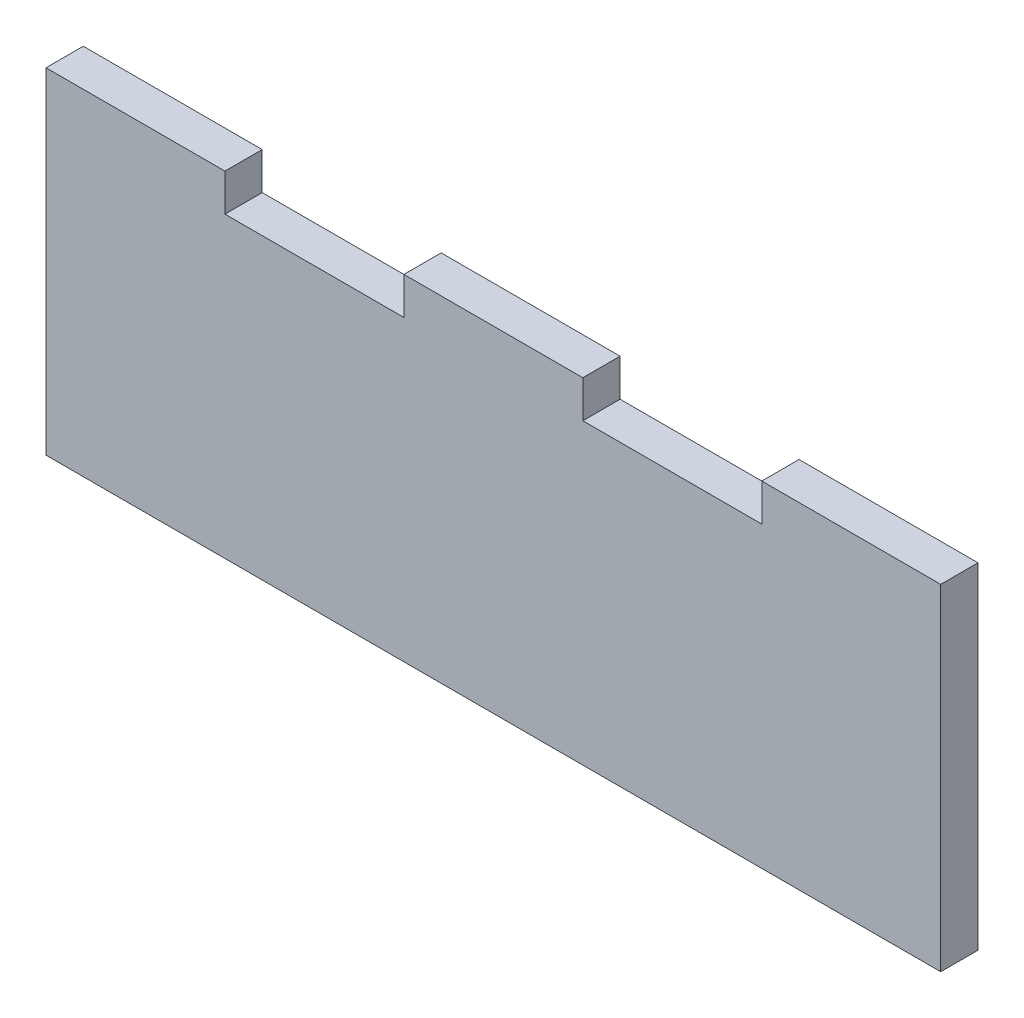
SolidWorks part; units mm, degrees
material "Pine"
ref_plane "Front Plane" through (0, 0, 0) normal (0, 0, 1) x (1, 0, 0)
ref_plane "Top Plane" through (0, 0, 0) normal (0, 1, 0) x (1, 0, 0)
ref_plane "Right Plane" through (0, 0, 0) normal (1, 0, 0) x (0, 0, -1)
sketch "Sketch2" plane through (0, 0, 0) normal (0, 0, 1) x (1, 0, 0)
  line L1 (0, 0) -> (152.4, 0)
  line L4 (91.44, 50.8) -> (91.44, 57.15)
  line L5 (91.44, 57.15) -> (60.96, 57.15)
  line L6 (60.96, 57.15) -> (60.96, 50.8)
  line L7 (60.96, 50.8) -> (30.48, 50.8)
  line L8 (30.48, 50.8) -> (30.48, 57.15)
  line L9 (30.48, 57.15) -> (0, 57.15)
  line L18 (152.4, 57.15) -> (121.92, 57.15)
  line L19 (121.92, 57.15) -> (121.92, 50.8)
  line L20 (121.92, 50.8) -> (91.44, 50.8)
  line L22 (0, 0) -> (0, 57.15)
  line L23 (152.4, 0) -> (152.4, 57.15)
  point P0 (121.92, 29.7347)
  dimension "D1" = 57.15
  dimension "D2" = 152.4
  dimension "D3" = 30.48
  dimension "D4" = 6.35
extrude "Boss-Extrude1" add sketch "Sketch2" along normal blind 6.35
